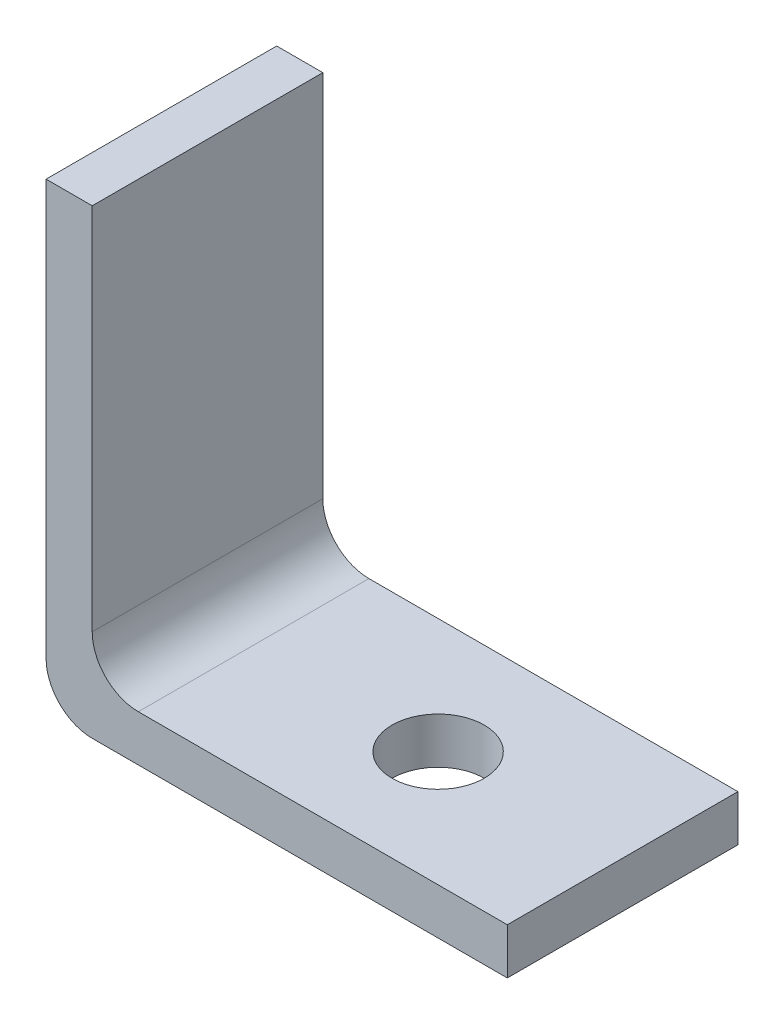
SolidWorks part; units mm, degrees
ref_plane "Front Plane" through (0, 0, 0) normal (0, 0, 1) x (1, 0, 0)
ref_plane "Top Plane" through (0, 0, 0) normal (0, 1, 0) x (1, 0, 0)
ref_plane "Right Plane" through (0, 0, 0) normal (1, 0, 0) x (0, 0, -1)
sketch "Sketch1" plane through (0, 0, 0) normal (0, 0, 1) x (1, 0, 0)
  line L0 (10, 0) -> (100, 0)
  line L1 (100, 0) -> (100, 10)
  line L2 (100, 10) -> (20, 10)
  line L3 (10, 20) -> (10, 100)
  line L4 (10, 100) -> (0, 100)
  line L5 (0, 100) -> (0, 10)
  arc A0 (10, 0) -> (0, 10) centre (10, 10) cw
  arc A1 (20, 10) -> (10, 20) centre (20, 20) cw
  point P9 (0, 0)
  dimension "D3" = 10
  dimension "D1" = 100
  dimension "D2" = 10
extrude "Boss-Extrude1" add sketch "Sketch1" along normal blind 50 contours L5 A0 L0 L1 L2 A1 L3 L4
sketch "Sketch2" plane through (0, 10, 0) normal (0, 1, 0) x (1, 0, 0)
  line L0 (100, -50) -> (20, -50) construction
  line L1 (100, -50) -> (100, 0) construction
  circle A0 centre (60, -25) radius 10
  dimension "D1" = 20
  dimension "D2" = 25
  dimension "D3" = 40
extrude "Cut-Extrude1" cut sketch "Sketch2" against normal up to surface (10 mm away) up to face at (55, 0, 25)
